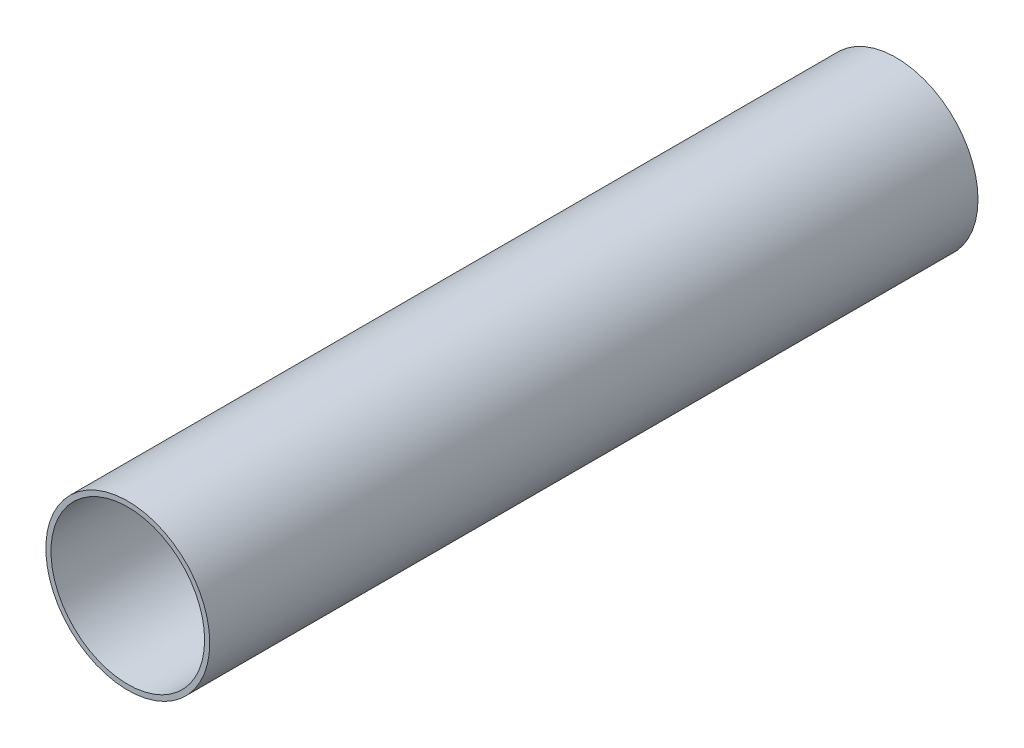
SolidWorks part; units mm, degrees
ref_plane "Front Plane" through (0, 0, 0) normal (0, 0, 1) x (1, 0, 0)
ref_plane "Top Plane" through (0, 0, 0) normal (0, 1, 0) x (1, 0, 0)
ref_plane "Right Plane" through (0, 0, 0) normal (1, 0, 0) x (0, 0, -1)
sketch "Sketch1" plane through (0, 0, 0) normal (0, 0, 1) x (1, 0, 0)
  circle A0 centre (0, 0) radius 19.05
  dimension "D1" = 38.1
extrude "Extrude-Thin1" add sketch "Sketch1" along normal blind 190.5 thin
